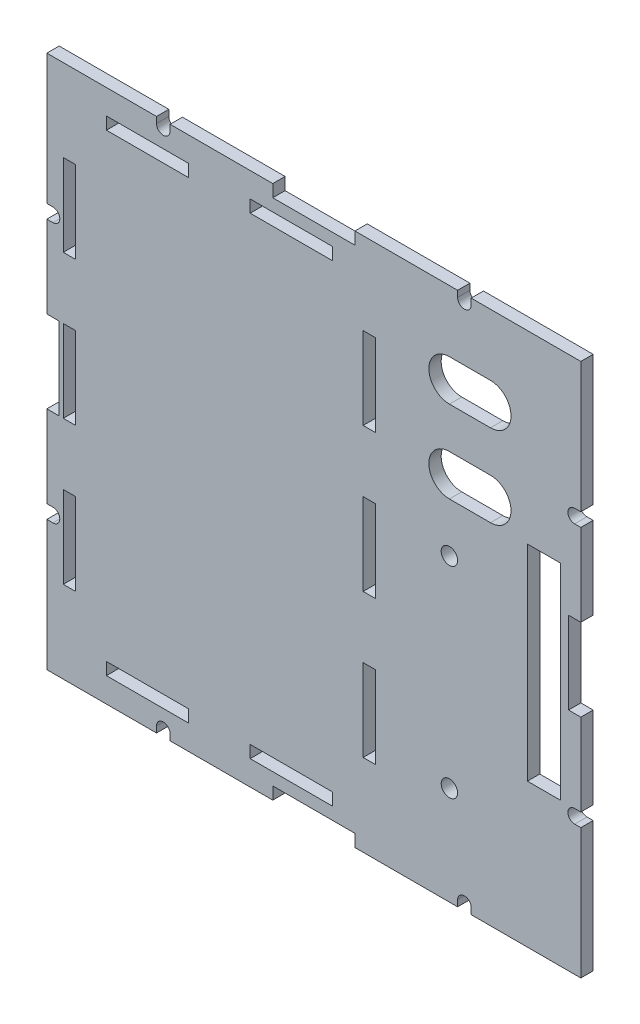
SolidWorks part; units mm, degrees
ref_plane "Front Plane" through (0, 0, 0) normal (0, 0, 1) x (1, 0, 0)
ref_plane "Top Plane" through (0, 0, 0) normal (0, 1, 0) x (1, 0, 0)
ref_plane "Right Plane" through (0, 0, 0) normal (1, 0, 0) x (0, 0, -1)
sketch "Sketch1" plane through (0, 0, 0) normal (0, 0, 1) x (1, 0, 0)
  line L0 (55, 0) -> (-55, 0) construction
  line L1 (65, -65) -> (-65, -65)
  line L2 (65, -65) -> (65, 65)
  line L3 (65, 65) -> (-65, 65)
  line L4 (-65, -65) -> (-65, 65)
  line L5 (65, -65) -> (-65, 65) construction
  line L6 (65, 65) -> (-65, -65) construction
  line L7 (10, 62) -> (-10, 62)
  line L8 (10, 62) -> (10, 65)
  line L9 (10, 65) -> (-10, 65)
  line L10 (-10, 62) -> (-10, 65)
  line L11 (10, 62) -> (-10, 65) construction
  line L12 (10, 65) -> (-10, 62) construction
  line L13 (-62, -10) -> (-65, -10)
  line L14 (-62, -10) -> (-62, 10)
  line L15 (-62, 10) -> (-65, 10)
  line L16 (-65, -10) -> (-65, 10)
  line L17 (-62, -10) -> (-65, 10) construction
  line L18 (-62, 10) -> (-65, -10) construction
  line L19 (10, -65) -> (-10, -65)
  line L20 (-10, -62) -> (-10, -65)
  line L21 (10, -62) -> (-10, -62)
  line L22 (10, -62) -> (10, -65)
  line L23 (0, -55) -> (0, 55) construction
  line L24 (62, 10) -> (65, 10)
  line L25 (65, -10) -> (65, 10)
  line L26 (62, -10) -> (65, -10)
  line L27 (62, -10) -> (62, 10)
  line L28 (-36.65, 63.5) -> (-36.65, 66.5) construction
  line L29 (-38.3, 63.5) -> (-38.3, 66.5)
  line L30 (-35, 63.5) -> (-35, 66.5)
  line L31 (-63.5, 31.65) -> (-66.5, 31.65) construction
  line L32 (-63.5, 30) -> (-66.5, 30)
  line L33 (-63.5, 33.3) -> (-66.5, 33.3)
  line L34 (36.65, 63.5) -> (36.65, 66.5) construction
  line L35 (38.3, 63.5) -> (38.3, 66.5)
  line L36 (35, 63.5) -> (35, 66.5)
  line L37 (63.5, 31.65) -> (66.5, 31.65) construction
  line L38 (63.5, 30) -> (66.5, 30)
  line L39 (63.5, 33.3) -> (66.5, 33.3)
  line L40 (63.5, -31.65) -> (66.5, -31.65) construction
  line L41 (63.5, -30) -> (66.5, -30)
  line L42 (63.5, -33.3) -> (66.5, -33.3)
  line L43 (36.65, -63.5) -> (36.65, -66.5) construction
  line L44 (38.3, -63.5) -> (38.3, -66.5)
  line L45 (35, -63.5) -> (35, -66.5)
  line L46 (-36.65, -63.5) -> (-36.65, -66.5) construction
  line L47 (-38.3, -63.5) -> (-38.3, -66.5)
  line L48 (-35, -63.5) -> (-35, -66.5)
  line L49 (-63.5, -31.65) -> (-66.5, -31.65) construction
  line L50 (-63.5, -30) -> (-66.5, -30)
  line L51 (-63.5, -33.3) -> (-66.5, -33.3)
  line L52 (-58, -45) -> (-61, -45)
  line L53 (-58, -10) -> (-61, -10)
  line L54 (-58, -10) -> (-58, 10)
  line L55 (-58, 10) -> (-61, 10)
  line L56 (-61, -10) -> (-61, 10)
  line L57 (-58, -10) -> (-61, 10) construction
  line L58 (-58, 10) -> (-61, -10) construction
  line L59 (-58, 25) -> (-61, 25)
  line L60 (-58, 25) -> (-58, 45)
  line L61 (-58, 45) -> (-61, 45)
  line L62 (-61, 25) -> (-61, 45)
  line L63 (-58, 25) -> (-61, 45) construction
  line L64 (-58, 45) -> (-61, 25) construction
  line L65 (-61, -25) -> (-61, -45)
  line L66 (-58, -25) -> (-61, -25)
  line L67 (-58, -25) -> (-58, -45)
  line L68 (-15.5, -59) -> (4.5, -59)
  line L69 (-30.5, 56) -> (-50.5, 56)
  line L70 (-30.5, 56) -> (-30.5, 59)
  line L71 (-30.5, 59) -> (-50.5, 59)
  line L72 (-50.5, 56) -> (-50.5, 59)
  line L73 (-30.5, 56) -> (-50.5, 59) construction
  line L74 (-30.5, 59) -> (-50.5, 56) construction
  line L75 (-15.5, 56) -> (4.5, 56)
  line L76 (-15.5, 56) -> (-15.5, 59)
  line L77 (-15.5, 59) -> (4.5, 59)
  line L78 (4.5, 56) -> (4.5, 59)
  line L79 (-15.5, 56) -> (4.5, 59) construction
  line L80 (-15.5, 59) -> (4.5, 56) construction
  line L81 (4.5, -56) -> (4.5, -59)
  line L82 (-15.5, -56) -> (4.5, -56)
  line L83 (-15.5, -56) -> (-15.5, -59)
  line L84 (-30.5, -59) -> (-50.5, -59)
  line L85 (-50.5, -56) -> (-50.5, -59)
  line L86 (-30.5, -56) -> (-50.5, -56)
  line L87 (-30.5, -56) -> (-30.5, -59)
  line L88 (33, 25) -> (43, 25) construction
  line L89 (12, 45) -> (15, 45)
  line L90 (12, 45) -> (12, 25)
  line L91 (12, 25) -> (15, 25)
  line L92 (15, 45) -> (15, 25)
  line L93 (12, 45) -> (15, 25) construction
  line L94 (12, 25) -> (15, 45) construction
  line L95 (15, -10) -> (12, -10)
  line L96 (15, -10) -> (15, 10)
  line L97 (15, 10) -> (12, 10)
  line L98 (12, -10) -> (12, 10)
  line L99 (15, -10) -> (12, 10) construction
  line L100 (15, 10) -> (12, -10) construction
  line L101 (12, -45) -> (15, -45)
  line L102 (12, -45) -> (12, -25)
  line L103 (12, -25) -> (15, -25)
  line L104 (15, -45) -> (15, -25)
  line L105 (12, -45) -> (15, -25) construction
  line L106 (12, -25) -> (15, -45) construction
  line L107 (60, -30) -> (52, -30)
  line L108 (60, -30) -> (60, 20)
  line L109 (60, 20) -> (52, 20)
  line L110 (52, -30) -> (52, 20)
  line L111 (60, -30) -> (52, 20) construction
  line L112 (60, 20) -> (52, -30) construction
  line L115 (33, 30) -> (43, 30)
  line L116 (33, 20) -> (43, 20)
  line L117 (43, 45) -> (33, 45) construction
  line L118 (43, 40) -> (33, 40)
  line L119 (43, 50) -> (33, 50)
  arc A0 (-38.3, 63.5) -> (-35, 63.5) centre (-36.65, 63.5) ccw
  arc A1 (-35, 66.5) -> (-38.3, 66.5) centre (-36.65, 66.5) ccw
  arc A2 (-63.5, 30) -> (-63.5, 33.3) centre (-63.5, 31.65) ccw
  arc A3 (-66.5, 33.3) -> (-66.5, 30) centre (-66.5, 31.65) ccw
  arc A4 (38.3, 63.5) -> (35, 63.5) centre (36.65, 63.5) cw
  arc A5 (35, 66.5) -> (38.3, 66.5) centre (36.65, 66.5) cw
  arc A6 (63.5, 30) -> (63.5, 33.3) centre (63.5, 31.65) cw
  arc A7 (66.5, 33.3) -> (66.5, 30) centre (66.5, 31.65) cw
  arc A8 (63.5, -30) -> (63.5, -33.3) centre (63.5, -31.65) ccw
  arc A9 (66.5, -33.3) -> (66.5, -30) centre (66.5, -31.65) ccw
  arc A10 (38.3, -63.5) -> (35, -63.5) centre (36.65, -63.5) ccw
  arc A11 (35, -66.5) -> (38.3, -66.5) centre (36.65, -66.5) ccw
  arc A12 (-38.3, -63.5) -> (-35, -63.5) centre (-36.65, -63.5) cw
  arc A13 (-35, -66.5) -> (-38.3, -66.5) centre (-36.65, -66.5) cw
  arc A14 (-63.5, -30) -> (-63.5, -33.3) centre (-63.5, -31.65) cw
  arc A15 (-66.5, -33.3) -> (-66.5, -30) centre (-66.5, -31.65) cw
  arc A18 (33, 30) -> (33, 20) centre (33, 25) ccw
  arc A19 (43, 20) -> (43, 30) centre (43, 25) ccw
  arc A20 (43, 40) -> (43, 50) centre (43, 45) ccw
  arc A21 (33, 50) -> (33, 40) centre (33, 45) ccw
  circle A22 centre (33, 8) radius 2
  circle A23 centre (33, -41) radius 2
  point P0 (0, 0)
  point P6 (0, 63.5)
  point P11 (-63.5, 0)
  point P16 (-36.65, 65)
  point P35 (-65, 31.65)
  point P42 (-59.5, 35)
  point P45 (36.65, 65)
  point P52 (65, 31.65)
  point P59 (65, -31.65)
  point P66 (36.65, -65)
  point P73 (-36.65, -65)
  point P80 (-65, -31.65)
  point P85 (-59.5, 0)
  point P94 (-5.5, 57.5)
  point P100 (-40.5, 57.5)
  point P108 (13.5, -35)
  point P117 (13.5, 35)
  point P123 (13.5, 0)
  point P132 (56, -5)
  point P138 (38, 25)
  point P143 (38, 45)
  dimension "D7" = 1.65
  dimension "D10" = 1.65
  dimension "D29" = 10
  dimension "D31" = 5
  dimension "D35" = 4
  dimension "D1" = 130
  dimension "D2" = 130
  dimension "D3" = 20
  dimension "D4" = 3
  dimension "D5" = 20
  dimension "D6" = 3
  dimension "D8" = 3
  dimension "D9" = 25
  dimension "D11" = 3
  dimension "D12" = 20
  dimension "D13" = 20
  dimension "D14" = 3
  dimension "D15" = 15
  dimension "D16" = 4
  dimension "D17" = 20
  dimension "D18" = 3
  dimension "D19" = 6
  dimension "D20" = 15
  dimension "D21" = 10.5
  dimension "D22" = 10.5
  dimension "D23" = 3
  dimension "D24" = 20
  dimension "D25" = 15
  dimension "D26" = 15
  dimension "D27" = 50
  dimension "D28" = 8
  dimension "5" = 35
  dimension "D30" = 5
  dimension "D32" = 15
  dimension "D33" = 27
  dimension "D34" = 10
  dimension "D36" = 8
  dimension "D37" = 49
  dimension "D38" = 33
extrude "Boss-Extrude1" add sketch "Sketch1" along normal blind 3 contours L26 L27 L24 L2 L3 L8 L7 L10 L4 L15 L14 L13 L1 L20 L21 L22
